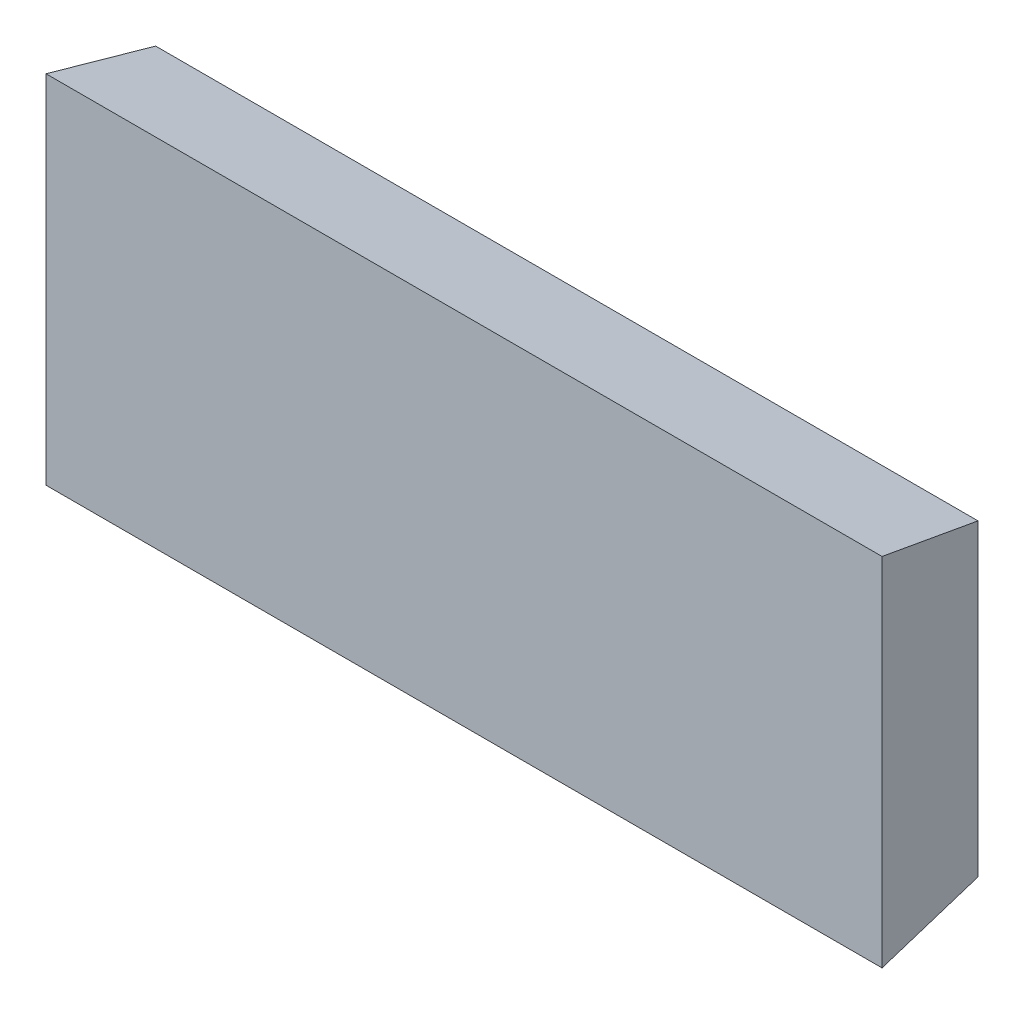
SolidWorks part; units mm, degrees
ref_plane "Ön Düzlem" through (0, 0, 0) normal (0, 0, 1) x (1, 0, 0)
ref_plane "Üst Düzlem" through (0, 0, 0) normal (0, 1, 0) x (1, 0, 0)
ref_plane "Sağ Düzlem" through (0, 0, 0) normal (1, 0, 0) x (0, 0, -1)
sketch "Sketch2" plane through (0, 0, 0) normal (1, 0, 0) x (0, 0, -1)
  line L0 (0, 30) -> (-10, 32.3333)
  line L1 (-10, 32.3333) -> (-10, -2.3333)
  line L2 (-10, -2.3333) -> (0, 0)
  line L3 (0, 0) -> (0, 30)
extrude "Boss-Extrude1" add sketch "Sketch2" along normal blind 80
sketch "Sketch4" plane through (0, 0, 0) normal (0, 1, 0) x (1, 0, 0)
  line L0 (0, 0) -> (0, -10)
  line L1 (0, -10) -> (-0.6667, -10)
  line L2 (-0.6667, -10) -> (0, 0)
  line L3 (40, -10) -> (40, 0) construction
  line L4 (80, -10) -> (0, -10) construction
  line L5 (80, 0) -> (0, 0) construction
  line L6 (80.6667, -10) -> (80, 0)
  line L7 (80, -10) -> (80.6667, -10)
  line L8 (80, 0) -> (80, -10)
extrude "Boss-Extrude2" add sketch "Sketch4" along normal up to surface and the other way up to surface up to face at (40, 31.1667, 5) other way up to face at (40, -1.1667, 5)
